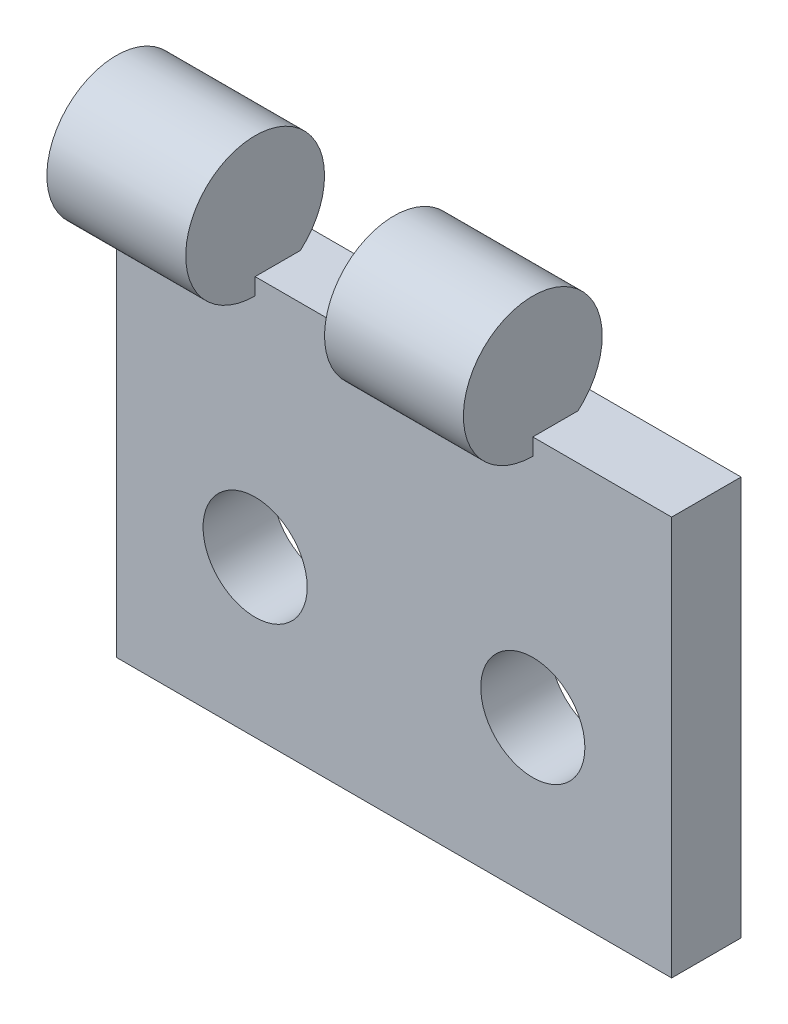
SolidWorks part; units mm, degrees
ref_plane "Front" through (0, 0, 0) normal (0, 0, 1) x (1, 0, 0)
ref_plane "Top" through (0, 0, 0) normal (0, 1, 0) x (1, 0, 0)
ref_plane "Right" through (0, 0, 0) normal (1, 0, 0) x (0, 0, -1)
sketch "Sketch1" plane through (0, 0, 0) normal (0, 0, 1) x (1, 0, 0)
  line L0 (0, 11.5) -> (0, 14.5) construction
  line L1 (0, 0) -> (16, 0)
  line L2 (0, 0) -> (0, 11.5)
  line L3 (0, 11.5) -> (16, 11.5)
  line L4 (16, 0) -> (16, 11.5)
  line L5 (0, 14.5) -> (16, 14.5) construction
  line L6 (16, 14.5) -> (16, 11.5) construction
  dimension "D1" = 16
  dimension "D2" = 14.5
  dimension "D3" = 3
extrude "Boss-Extrude1" add sketch "Sketch1" along normal blind 2
sketch "Sketch2" plane through (0, 0, 0) normal (1, 0, 0) x (0, 0, -1)
  line L0 (0, 11.5) -> (0, 13.0179) construction
  circle A0 centre (-2, 13.0179) radius 2
  dimension "D1" = 4
extrude "Boss-Extrude2" add sketch "Sketch2" along normal blind 4
pattern_linear "LPattern1" count 2 spacing 8 along (1, 0, 0) of "Boss-Extrude2"
hole_wizard "Ø3.0mm Dowel Hole1" positions "Sketch3" profile "Sketch4" hole size "Ø3.0" standard "ANSI Metric" end condition through all
sketch "Sketch3" plane through (0, 0, 2) normal (0, 0, 1) x (1, 0, 0)
  line L0 (0, 11.0179) -> (0, 0) construction
  line L1 (16, 0) -> (16, 11.5) construction
  line L2 (8, 11.5) -> (4, 11.5) construction
  point P0 (4, 4.5)
  point P2 (12, 4.5)
  dimension "D1" = 4
  dimension "D2" = 4
  dimension "D3" = 7
sketch "Sketch4" plane through (4, 4.5, 2) normal (1, 0, 0) x (0, -1, 0)
  line L0 (0, 0) -> (0, 2)
  line L1 (0, 2) -> (1.5, 2)
  line L2 (1.5, 2) -> (1.5, 0)
  line L5 (1.5, 0) -> (0, 0)
  line L11 (0, -6.35) -> (0, 107.95) construction
  dimension "Thru Hole Dia." = 3
  dimension "Thru Hole Depth" = 2
